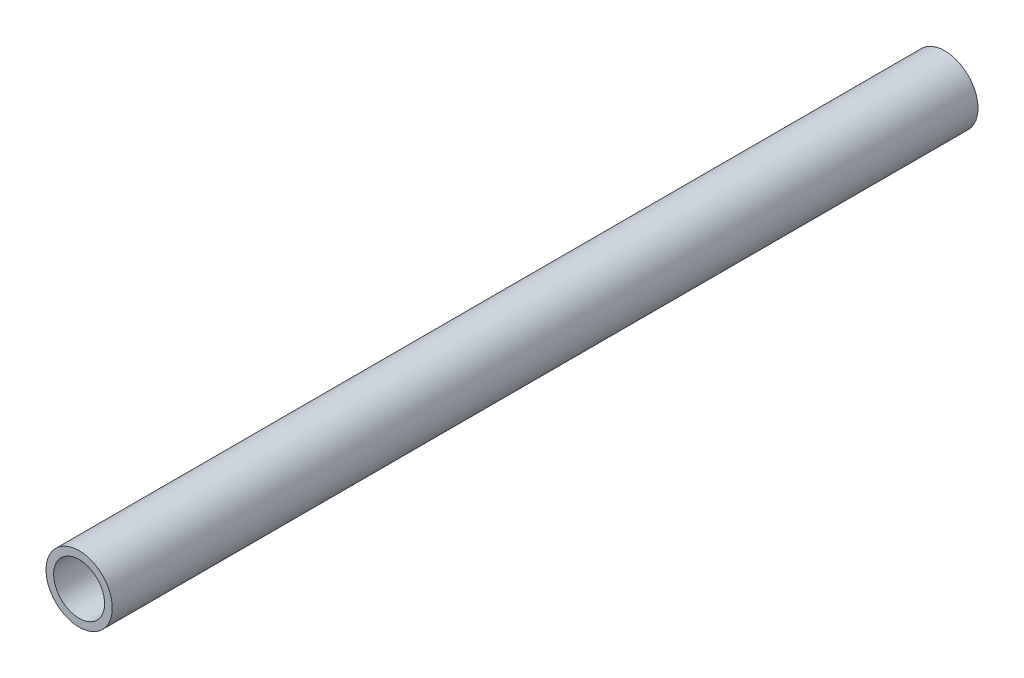
SolidWorks part; units mm, degrees
ref_plane "Front Plane" through (0, 0, 0) normal (0, 0, 1) x (1, 0, 0)
ref_plane "Top Plane" through (0, 0, 0) normal (0, 1, 0) x (1, 0, 0)
ref_plane "Right Plane" through (0, 0, 0) normal (1, 0, 0) x (0, 0, -1)
sketch "Sketch1" plane through (0, 0, 0) normal (0, 0, 1) x (1, 0, 0)
  circle A0 centre (0, 0) radius 16.51
  circle A1 centre (0, 0) radius 12.7
  dimension "D1" = 33.02
  dimension "D2" = 25.4
extrude "Boss-Extrude1" add sketch "Sketch1" along normal up to surface (431.292 mm away)
ref_plane "Fitting2" through (0, 0, 431.292) normal (0, 0, 1) x (1, 0, 0)
ref_plane "Fitting1" through (0, 0, 0) normal (0, 0, 1) x (1, 0, 0)
